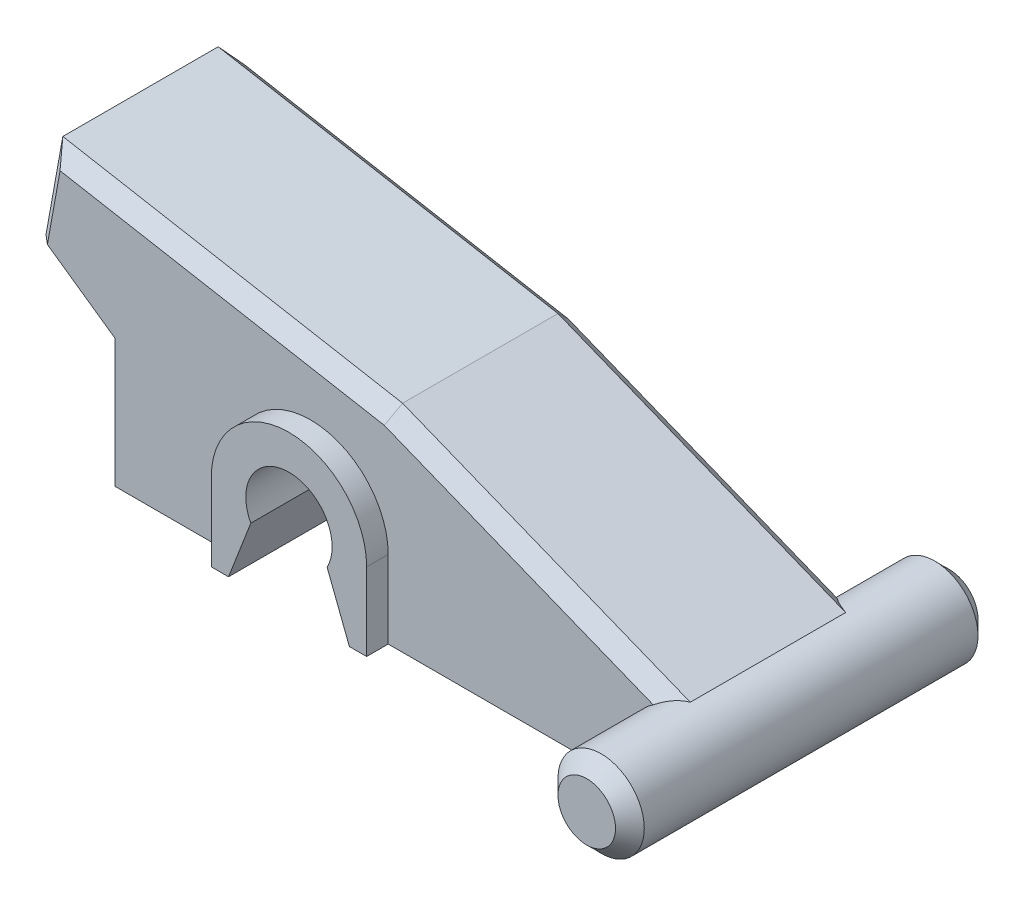
SolidWorks part; units mm, degrees
ref_plane "Front Plane" through (0, 0, 0) normal (0, 0, 1) x (1, 0, 0)
ref_plane "Top Plane" through (0, 0, 0) normal (0, 1, 0) x (1, 0, 0)
ref_plane "Right Plane" through (0, 0, 0) normal (1, 0, 0) x (0, 0, -1)
sketch "Sketch1" plane through (0, 0, 0) normal (0, 0, 1) x (1, 0, 0)
  line L0 (10, -4.4) -> (10, -1.4)
  line L1 (-10, -4.4) -> (10, -4.4)
  line L2 (-10, -4.4) -> (-10, 4.4)
  line L3 (-10, 4.4) -> (10, 4.4)
  line L4 (10, -4.4) -> (10, 4.4)
  line L5 (-10, -4.4) -> (10, 4.4) construction
  line L6 (-10, 4.4) -> (10, -4.4) construction
  line L7 (10, -1.4) -> (0, 2.6)
  line L8 (0, 2.6) -> (-11.8102, 4.7258)
  line L9 (-11.8102, 4.7258) -> (-12.3948, 1.478)
  line L10 (-12.3948, 1.478) -> (-10, -0.2)
  point P0 (0, 0)
  dimension "D1" = 20
  dimension "D2" = 8.8
  dimension "D3" = 3
  dimension "D4" = 7
  dimension "D5" = 10
  dimension "D6" = 12
  dimension "D7" = 3.3
  dimension "D8" = 4.2
extrude "Boss-Extrude1" add sketch "Sketch1" along normal mid plane 6.4 contours L7 L8 L2 L1 L0 | L9 L10 L2 L8
sketch "Sketch2" plane through (0, 0, 3.2) normal (0, 0, 1) x (1, 0, 0)
  line L0 (-10, -4.4) -> (10, -4.4) construction
  line L1 (-10, -4.4) -> (-10, -0.2) construction
  line L2 (-5.4, -1.7) -> (-5.4, -4.4)
  line L3 (-5.4, -4.4) -> (-2.7, -4.4)
  line L4 (-2.7, -4.4) -> (-5.4, -1.7)
  line L5 (-2.7, -4.4) -> (0, -4.4)
  line L6 (0, -4.4) -> (0, -1.7)
  line L7 (0, -1.7) -> (-2.7, -4.4)
  circle A0 centre (-2.7, -1.7) radius 2.7
  line M13 (-10, -4.4) -> (10, -4.4)
  dimension "D1" = 5.4
  dimension "D2" = 7.3
extrude "Boss-Extrude2" add sketch "Sketch2" along normal mid plane 1.5 contours L7 A0 L4 | L4 A0 | L7 A0 | A0 L6 M13 | A0 L2 M13
mirror "Mirror1" about plane through (0, 0, 0) normal (0, 0, 1) of "Boss-Extrude2"
sketch "Sketch3" plane through (0, 0, 3.95) normal (0, 0, 1) x (1, 0, 0)
  line L0 (-4.8, -4.4) -> (-0.6, -4.4)
  line L1 (-5.4, -4.4) -> (0, -4.4) construction
  line L2 (-4.8, -4.4) -> (-4.0266, -2.4)
  line L3 (-4.0266, -2.4) -> (-1.3734, -2.4)
  line L4 (-1.3734, -2.4) -> (-0.6, -4.4)
  circle A0 centre (-2.7, -1.7) radius 1.5
  point P8 (-2.7, -4.4)
  line M5 (-5.4, -4.4) -> (0, -4.4)
  dimension "D1" = 3
  dimension "D2" = 4.2
  dimension "D3" = 0
  dimension "D4" = 2
extrude "Cut-Extrude1" cut sketch "Sketch3" against normal through all both and the other way through all contours L3 A0 | A0 L2 L4 M5
sketch "Sketch4" plane through (0, 0, 0) normal (0, 0, 1) x (1, 0, 0)
  line L0 (10, -4.4) -> (10, -1.4) construction
  circle A0 centre (10, -2.9) radius 1.5
extrude "Boss-Extrude3" add sketch "Sketch4" along normal mid plane 12.6
chamfer "Chamfer1" distance 0.5 angle 45 2 edges at (11.5, -2.9, -6.3) (11.5, -2.9, 6.3)
chamfer "Chamfer2" distance 0.5 angle 45 10 edges at (-10, -2.3, -3.2) (-10, -2.3, 3.2) (-11.1974, 0.639, -3.2) (-11.1974, 0.639, 3.2) (-12.1025, 3.1019, -3.2) (-12.1025, 3.1019, 3.2) (-5.9051, 3.6629, -3.2) (-5.9051, 3.6629, 3.2) (5, 0.6, -3.2) (5, 0.6, 3.2)
sketch "Sketch5" plane through (0, 0, 3.2) normal (0, 0, 1) x (1, 0, 0)
  line L0 (-10.5291, 2.2466) -> (-10.4382, 2.7516)
  line L1 (-10.4382, 2.7516) -> (-0.4711, 0.9575)
  line L2 (-0.4711, 0.9575) -> (7.3953, -2.1891)
  line L3 (7.3167, -3.2) -> (0, -3.2)
  line L4 (0, -1.7) -> (0, -4.4) construction
  line L5 (-10.5291, 2.2466) -> (-8.3, 0.6846)
  line L6 (-8.3, 0.6846) -> (-8.3, -3.2)
  line L7 (-8.3, -3.2) -> (-5.4, -3.2)
  line L8 (-5.4, -4.4) -> (-5.4, -1.7) construction
  line L9 (-11.4067, 4.1452) -> (-11.8461, 1.7041) construction
  line L10 (-0.1386, 2.1169) -> (-11.4067, 4.1452) construction
  line L11 (9.2123, -1.6234) -> (-0.1386, 2.1169) construction
  line L12 (0, -4.4) -> (10, -4.4) construction
  line L15 (-9.5, -4.4) -> (-5.4, -4.4) construction
  line L16 (-9.5, 0.0602) -> (-9.5, -4.4) construction
  line L17 (-11.8461, 1.7041) -> (-9.5, 0.0602) construction
  line L18 (-5.4, -3.2) -> (-5.4, -1.7)
  line L19 (0, -3.2) -> (0, -1.7)
  circle A0 centre (10, -2.9) radius 2.7
  circle A1 centre (10, -2.9) radius 1.5 construction
  circle A2 centre (-2.7, -1.7) radius 2.7
  line M14 (-5.4, -4.4) -> (-5.4, -1.7)
  arc M15 (-5.4, -1.7) -> (0, -1.7) centre (-2.7, -1.7) cw
  line M16 (0, -1.7) -> (0, -4.4)
  dimension "D4" = 1.2
  dimension "D9" = 5.4
  dimension "D1" = 1.2
  dimension "D2" = 1.2
  dimension "D3" = 1.2
  dimension "D5" = 1.2
  dimension "D6" = 1.2
  dimension "D7" = 1.2
  dimension "D8" = 1.2
extrude "Cut-Extrude2" cut sketch "Sketch5" against normal offset from surface (5.2 mm away) 1.2 contours A0 L2 L1 L0 L5 L6 L7 L3 M14 M15 M16 up to face at (-3.1844, -1.1086, -3.2)
mirror "Mirror2" about plane through (0, 0, 3.2) normal (0, 0, 1) of bodies 107
delete or keep bodies "-1" type delete bodies bodies 107
